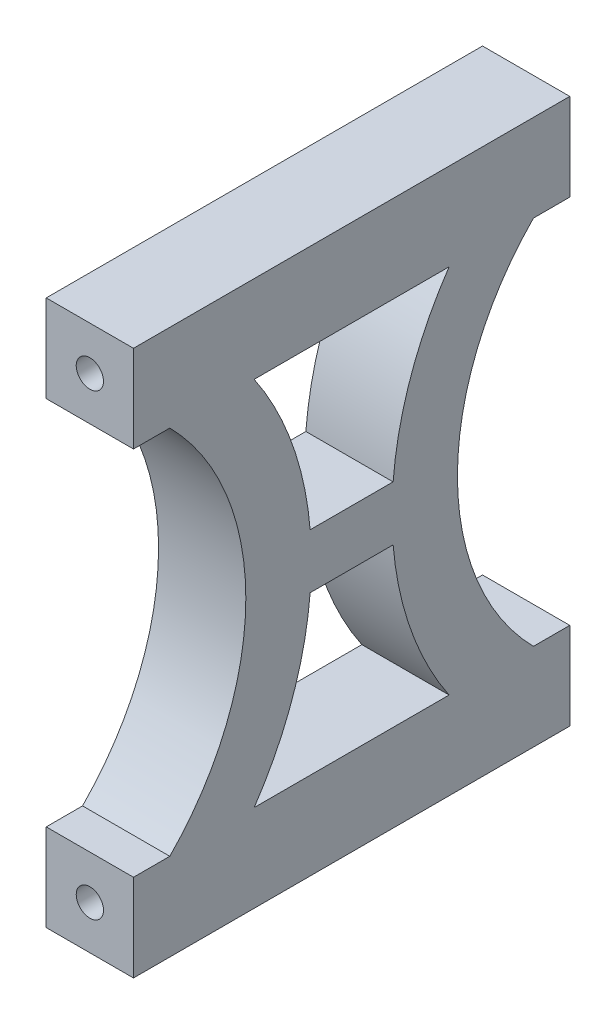
SolidWorks part; units mm, degrees
ref_plane "Front Plane" through (0, 0, 0) normal (0, 0, 1) x (1, 0, 0)
ref_plane "Top Plane" through (0, 0, 0) normal (0, 1, 0) x (1, 0, 0)
ref_plane "Right Plane" through (0, 0, 0) normal (1, 0, 0) x (0, 0, -1)
sketch "Sketch1" plane through (0, 0, 0) normal (0, 0, 1) x (1, 0, 0)
  line L0 (0, 0) -> (0, 21) construction
  line L1 (-4, 25) -> (4, 25)
  line L2 (-4, 25) -> (-4, 17)
  line L3 (-4, 17) -> (4, 17)
  line L4 (4, 25) -> (4, 17)
  line L5 (-4, 25) -> (4, 17) construction
  line L6 (-4, 17) -> (4, 25) construction
  line L7 (0, 0) -> (5.9978, 0) construction
  line L8 (-4, -17) -> (4, -25) construction
  line L9 (-4, -25) -> (4, -17) construction
  line L10 (4, -25) -> (4, -17)
  line L11 (-4, -17) -> (4, -17)
  line L12 (-4, -25) -> (-4, -17)
  line L13 (-4, -25) -> (4, -25)
  circle A0 centre (0, 21) radius 1.25
  circle A1 centre (0, -21) radius 1.25
  point P0 (0, 21)
extrude "Boss-Extrude1" add sketch "Sketch1" along normal blind 40
sketch "Sketch2" plane through (-4, 0, 0) normal (-1, 0, 0) x (0, 0, 1)
  line L0 (20, 27.6501) -> (20, -26.4609) construction
  line L1 (40, 17) -> (0, 17) construction
  line L2 (40, -17) -> (0, -17) construction
  line L3 (3.3296, 17) -> (11.064, 17)
  line L4 (3.3296, -17) -> (11.064, -17)
  line L5 (36.6704, -17) -> (28.936, -17)
  line L6 (23.8046, -2.5089) -> (16.1954, -2.5089)
  line L7 (36.6704, 17) -> (28.936, 17)
  line L8 (23.8031, 2.4911) -> (16.1969, 2.4911)
  arc A0 (3.3296, 17) -> (3.3296, -17) centre (-13.9166, 0) cw
  arc A1 (11.064, 17) -> (16.1969, 2.4911) centre (-13.9166, 0) cw
  arc A2 (16.1954, -2.5089) -> (11.064, -17) centre (-13.9166, 0) cw
  arc A3 (7.6027, 21.212) -> (7.6027, -21.212) centre (-13.9166, 0) cw construction
  arc A4 (23.8046, -2.5089) -> (28.936, -17) centre (53.9166, 0) ccw
  arc A5 (28.936, 17) -> (23.8031, 2.4911) centre (53.9166, 0) ccw
  arc A6 (36.6704, 17) -> (36.6704, -17) centre (53.9166, 0) ccw
  point P12 (20, -0.0089)
  point P22 (20, -2.5089)
  point P27 (20, 2.4911)
  dimension "D1" = 6
extrude "Boss-Extrude2" add sketch "Sketch2" against normal blind 8
